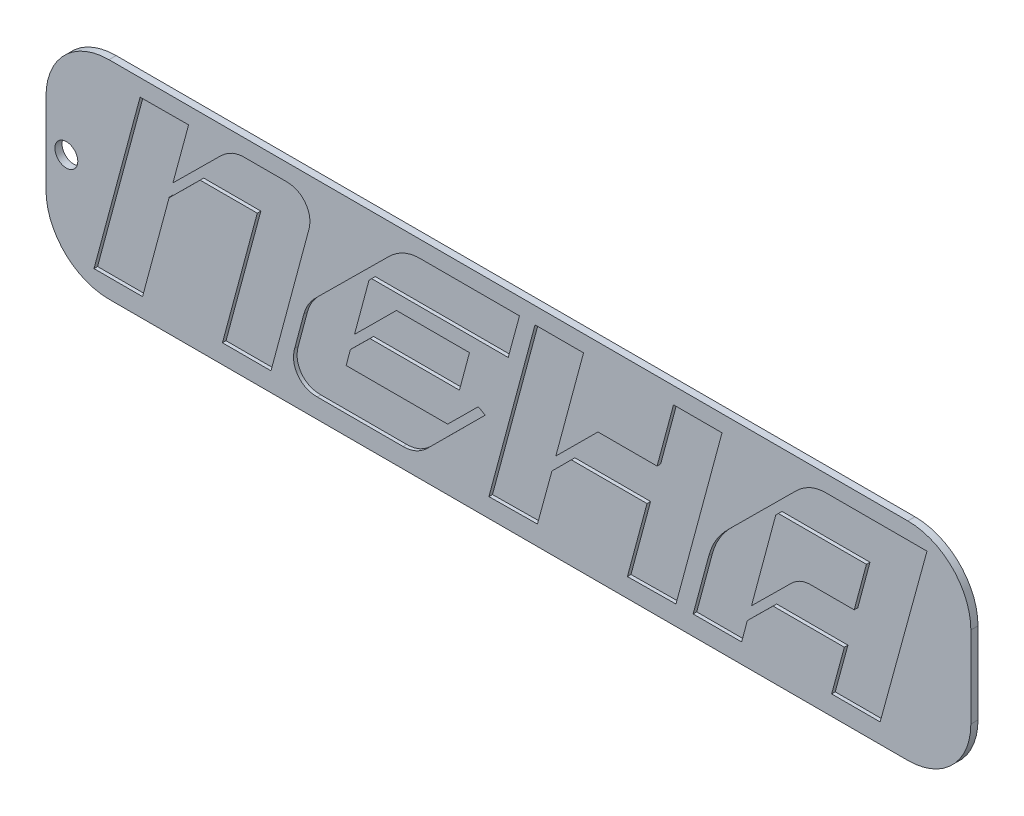
SolidWorks part; units mm, degrees
ref_plane "Front Plane" through (0, 0, 0) normal (0, 0, 1) x (1, 0, 0)
ref_plane "Top Plane" through (0, 0, 0) normal (0, 1, 0) x (1, 0, 0)
ref_plane "Right Plane" through (0, 0, 0) normal (1, 0, 0) x (0, 0, -1)
sketch "Sketch1" plane through (0, 0, 0) normal (0, 0, 1) x (1, 0, 0)
  line L0 (-26.2857, 37.4583) -> (-17.2664, 37.4583) construction
  line L1 (1.6543, 83.4569) -> (355.9284, 83.4569)
  line L2 (-26.2857, 55.5169) -> (-26.2857, 19.3997)
  line L3 (1.6543, -8.5403) -> (355.9284, -8.5403)
  line L4 (383.8684, 55.5169) -> (383.8684, 19.3997)
  arc A0 (355.9284, 83.4569) -> (383.8684, 55.5169) centre (355.9284, 55.5169) cw
  arc A1 (355.9284, -8.5403) -> (383.8684, 19.3997) centre (355.9284, 19.3997) ccw
  arc A2 (-26.2857, 19.3997) -> (1.6543, -8.5403) centre (1.6543, 19.3997) ccw
  arc A3 (1.6543, 83.4569) -> (-26.2857, 55.5169) centre (1.6543, 55.5169) ccw
  circle A4 centre (-17.2664, 37.4583) radius 5.08
  text T0 "neha" font "Sterion" height 76.2
  dimension "D1" = 27.94
extrude "Boss-Extrude1" add sketch "Sketch1" along normal blind 3.175
sketch "Sketch2" plane through (0, 0, 3.175) normal (0, 0, 1) x (1, 0, 0)
  text T0 "neha" font "Sterion" height 76.2
extrude "Cut-Extrude1" cut sketch "Sketch2" against normal blind 1.5875
